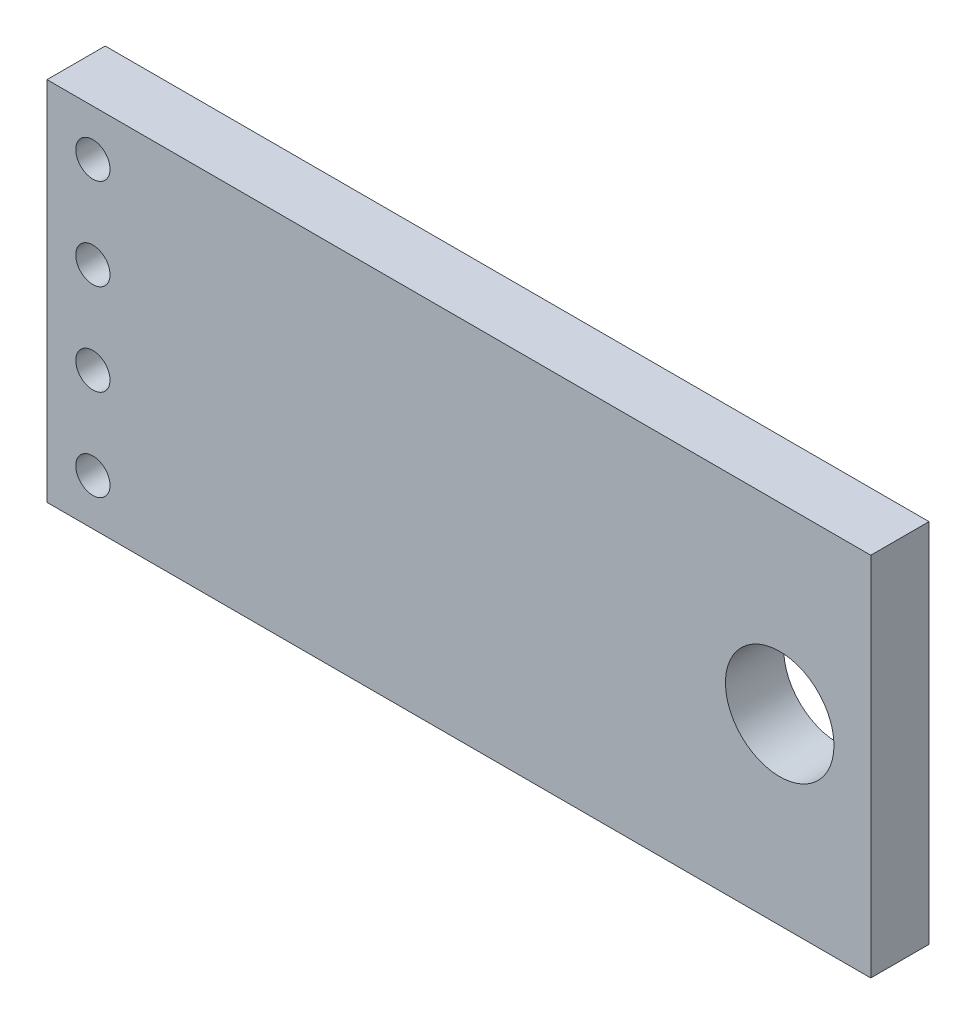
SolidWorks part; units mm, degrees
ref_plane "Front Plane" through (0, 0, 0) normal (0, 0, 1) x (1, 0, 0)
ref_plane "Top Plane" through (0, 0, 0) normal (0, 1, 0) x (1, 0, 0)
ref_plane "Right Plane" through (0, 0, 0) normal (1, 0, 0) x (0, 0, -1)
other "Mesh1"
other "Imported Mesh-1"
other "Imported Mesh-2"
other "Imported Mesh-3"
other "Imported Mesh-4"
other "Imported Mesh-5"
other "Imported Mesh-6"
other "Imported Mesh-7"
other "Imported Mesh-8"
other "Imported Mesh-9"
sketch "Sketch1" plane through (0, 0, 0) normal (0, 0, 1) x (1, 0, 0)
  line L0 (1.2765, 10.1849) -> (1.2765, 8.9021) construction
  line L1 (22.9172, -0.0007) -> (0, -0.0007)
  line L2 (22.9172, -0.0007) -> (22.9172, 10.1849)
  line L3 (22.9172, 10.1849) -> (0, 10.1849)
  line L4 (0, -0.0007) -> (0, 10.1849)
  line L5 (22.9172, -0.0007) -> (0, 10.1849) construction
  line L6 (22.9172, 10.1849) -> (0, -0.0007) construction
  line L7 (1.2765, 8.9021) -> (1.2765, 6.3621) construction
  line L8 (1.2765, 6.3621) -> (1.2765, 3.8221) construction
  line L9 (1.2765, 3.8221) -> (1.2765, 1.2821) construction
  line L10 (1.2765, 1.2821) -> (1.2765, -0.0007) construction
  circle A0 centre (20.3838, 5.0921) radius 1.5098
  circle A1 centre (1.2765, 8.9021) radius 0.4766
  circle A2 centre (1.2765, 6.3621) radius 0.4766
  circle A3 centre (1.2765, 3.8221) radius 0.4766
  circle A4 centre (1.2765, 1.2821) radius 0.4766
  point P0 (11.4586, 5.0921)
  dimension "D1" = 2.54
extrude "Boss-Extrude1" add sketch "Sketch1" along normal mid plane 1.62
